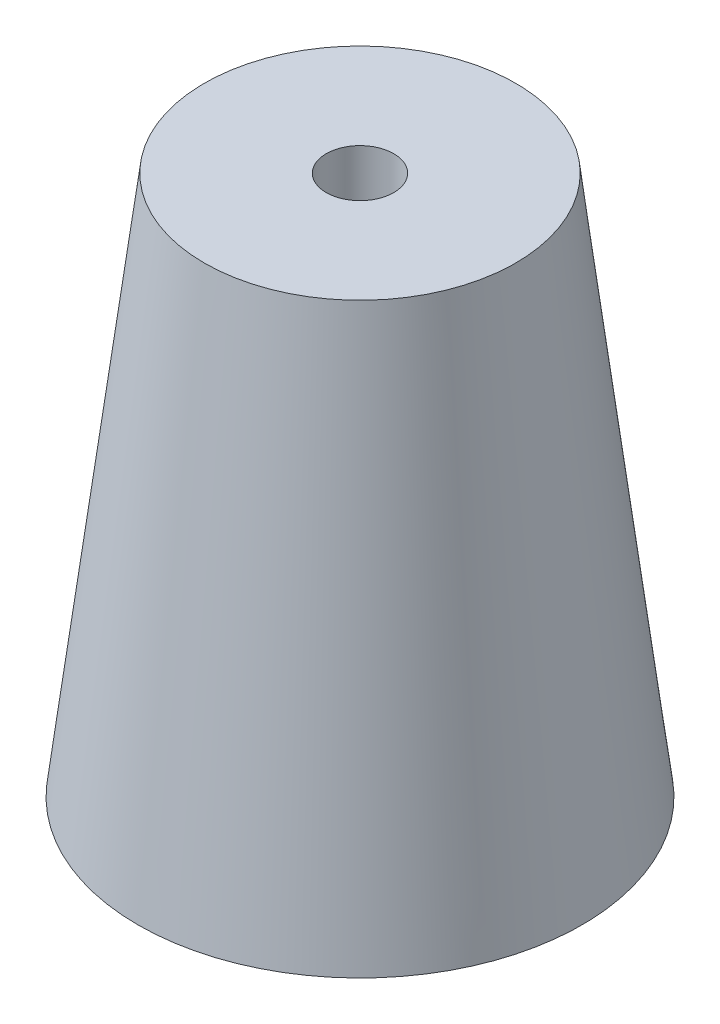
SolidWorks part; units mm, degrees
material "Pure Lead"
ref_plane "Front Plane" through (0, 0, 0) normal (0, 0, 1) x (1, 0, 0)
ref_plane "Top Plane" through (0, 0, 0) normal (0, 1, 0) x (1, 0, 0)
ref_plane "Right Plane" through (0, 0, 0) normal (1, 0, 0) x (0, 0, -1)
sketch "Sketch1" plane through (0, 0, 0) normal (0, 1, 0) x (1, 0, 0)
  circle A0 centre (0, 0) radius 23.495
  dimension "D1" = 46.99
extrude "Boss-Extrude1" add sketch "Sketch1" along normal blind 57.15 draft 7
hole_wizard "1/4 Clearance Hole1" positions "Sketch3" profile "Sketch2" hole size "1/4" standard "ANSI Inch" end condition through all
sketch "Sketch3" plane through (0, 0, 0) normal (0, -1, 0) x (-1, 0, 0)
  point P0 (0, 0)
sketch "Sketch2" plane through (0, 0, 0) normal (1, 0, 0) x (0, 0, -1)
  line L0 (0, 0) -> (0, 57.15)
  line L1 (0, 57.15) -> (3.5712, 57.15)
  line L2 (3.5712, 57.15) -> (3.5712, 0)
  line L5 (3.5712, 0) -> (0, 0)
  line L11 (0, -6.35) -> (0, 107.95) construction
  dimension "Thru Hole Dia." = 7.1425
  dimension "Thru Hole Depth" = 57.15
